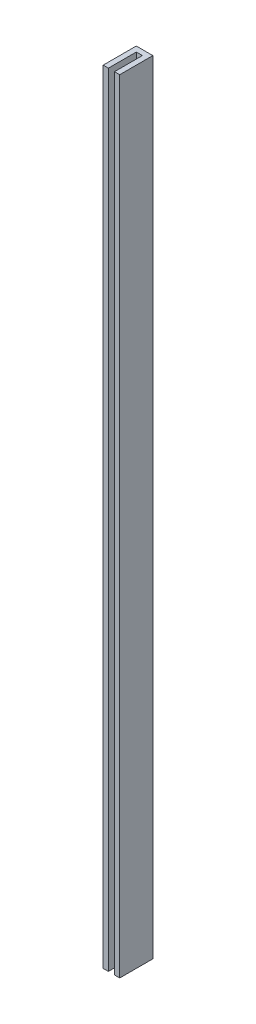
SolidWorks part; units mm, degrees
material "5052-H32"
ref_plane "Plano frontal" through (0, 0, 0) normal (0, 0, 1) x (1, 0, 0)
ref_plane "Plano superior" through (0, 0, 0) normal (0, 1, 0) x (1, 0, 0)
ref_plane "Plano direito" through (0, 0, 0) normal (1, 0, 0) x (0, 0, -1)
sketch "Esboço1" plane through (0, 0, 0) normal (0, 1, 0) x (1, 0, 0)
  line L0 (0, 2.6272) -> (0, -15.2545) construction
  line L1 (3.175, 0) -> (-3.175, 0)
  line L2 (-3.175, 0) -> (-3.175, -12.7)
  line L3 (3.175, 0) -> (3.175, -12.7)
  line L4 (-3.175, -12.7) -> (-1.175, -12.7)
  line L5 (-1.175, -12.7) -> (-1.175, -2)
  line L6 (-1.175, -2) -> (1.175, -2)
  line L7 (3.175, -12.7) -> (1.175, -12.7)
  line L8 (1.175, -12.7) -> (1.175, -2)
  line L9 (-1.175, -2) -> (-1.175, 0) construction
  dimension "D1" = 12.7
  dimension "D2" = 6.35
  dimension "D4" = 2.35
  dimension "x" = 2
extrude "Ressalto-extrusão1" add sketch "Esboço1" along normal blind 300
equation "\"x\" = 10mm"
